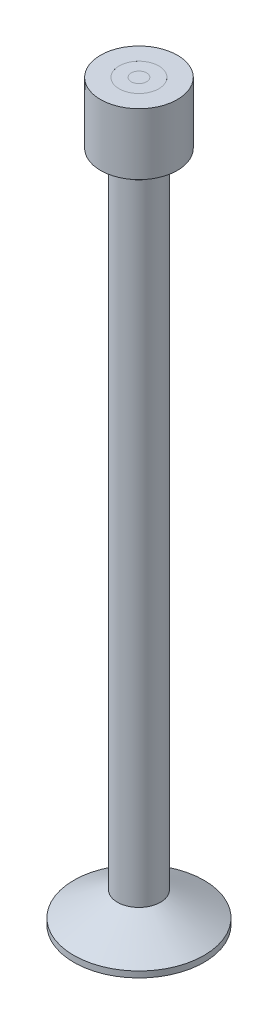
SolidWorks part; units mm, degrees
ref_plane "Alzado" through (0, 0, 0) normal (0, 0, 1) x (1, 0, 0)
ref_plane "Planta" through (0, 0, 0) normal (0, 1, 0) x (1, 0, 0)
ref_plane "Vista lateral" through (0, 0, 0) normal (1, 0, 0) x (0, 0, -1)
sketch "Croquis1" plane through (0, 0, 0) normal (0, 0, 1) x (1, 0, 0)
  line L0 (0, -22.5273) -> (0, 60.571) construction
  line L1 (5.375, 0) -> (5.375, 0.5)
  line L2 (5.375, 0.5) -> (1.78, 2.5)
  line L3 (1.78, 2.5) -> (1.78, 54.5)
  line L4 (1.78, 54.5) -> (3.1718, 55.5)
  line L5 (3.1718, 55.5) -> (3.1718, 60.571)
  line L6 (1.375, 54.9422) -> (1.375, 0)
  line L7 (1.375, 0) -> (5.375, 0)
  line L8 (0.375, 0) -> (0.375, 54.9422)
  line L9 (0.375, 54.9422) -> (0.635, 60.571)
  line L10 (0.375, 0) -> (0, 0)
  line L11 (0, 60.571) -> (0, 0)
  line L12 (0, 60.9797) -> (0, 62.2297) construction
  line L13 (3.1718, 60.571) -> (1.635, 60.571)
  line L14 (0.4604, 60.571) -> (-0.4604, 60.571) construction
  line L23 (1.375, 54.9422) -> (1.635, 60.571)
  line L26 (0.635, 60.571) -> (0.4424, 60.571)
  line L27 (0.4424, 60.571) -> (0, 60.571)
  point P16 (0, 0)
  point P21 (0, 0)
  point P24 (3.1529, 60.6297)
  point P25 (3.1718, 55.5)
  point P27 (3.1729, 60.571)
  point P28 (3.174, 60.571)
  dimension "D1" = 55
  dimension "D2" = 10.75
  dimension "D3" = 2
  dimension "D4" = 0.5
  dimension "D5" = 0.75
  dimension "D6" = 2.75
  dimension "D7" = 3.56
  dimension "D8" = 1
revolve "Revolución1" add sketch "Croquis1" angle 360 about L11
sketch "Croquis3" plane through (0, 0, 0) normal (0, 0, 1) x (1, 0, 0)
  line L0 (0, 55.5) -> (0, 0) construction
  line L1 (0.375, 54.9422) -> (0.635, 60.571)
  line L2 (0.635, 60.571) -> (-0.635, 60.571) construction
  line L3 (0.635, 60.571) -> (-0.635, 60.571) construction
  line L4 (0.635, 60.571) -> (1.635, 60.571)
  line L6 (0.635, 60.571) -> (0.4424, 60.571)
  line L7 (0.375, 0) -> (0.375, 54.9422)
  line L8 (0, 0) -> (0.375, 0)
  line L9 (0, 60.571) -> (0, 0)
  line L10 (0.375, 54.9422) -> (0.635, 60.571)
  line L12 (0.4424, 60.571) -> (0, 60.571)
  line L13 (0.375, 0) -> (0.375, 54.9422)
  line L20 (3.1718, 55.5) -> (3.1718, 60.571)
  line L21 (1.78, 54.5) -> (3.1718, 55.5)
  line L22 (1.78, 2.5) -> (1.78, 54.5)
  line L23 (5.375, 0.5) -> (1.78, 2.5)
  line L24 (5.375, 0) -> (5.375, 0.5)
  line L25 (1.375, 0) -> (5.375, 0)
  line L26 (1.375, 54.9422) -> (1.375, 0)
  line L27 (1.635, 60.571) -> (1.375, 54.9422)
  line L28 (1.635, 60.571) -> (1.375, 54.9422)
  line L29 (3.1718, 60.571) -> (1.635, 60.571)
  line L33 (0.375, 0) -> (1.375, 0)
  line L34 (1.375, 54.9422) -> (1.375, 0)
  dimension "D1" = 0
  dimension "D2" = 0
revolve "Revolución2" add sketch "Croquis3" angle 360 about L0
